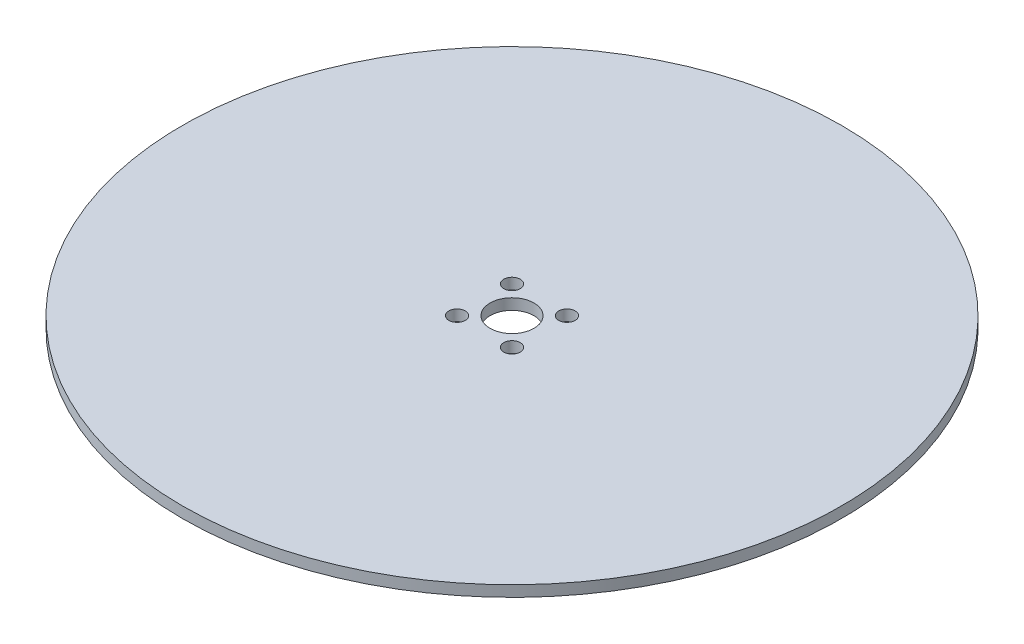
SolidWorks part; units mm, degrees
ref_plane "前视基准面" through (0, 0, 0) normal (0, 0, 1) x (1, 0, 0)
ref_plane "上视基准面" through (0, 0, 0) normal (0, 1, 0) x (1, 0, 0)
ref_plane "右视基准面" through (0, 0, 0) normal (1, 0, 0) x (0, 0, -1)
other "Configuration Table"
sketch "草图1" plane through (0, 0, 0) normal (0, 1, 0) x (1, 0, 0)
  circle A0 centre (0, 0) radius 60
  dimension "D1" = 120
extrude "凸台-拉伸1" add sketch "草图1" along normal blind 2
sketch "草图2" plane through (0, 2, 0) normal (0, 1, 0) x (1, 0, 0)
  line L1 (5, -5) -> (-5, -5)
  line L2 (5, -5) -> (5, 5)
  line L3 (5, 5) -> (-5, 5)
  line L4 (-5, -5) -> (-5, 5)
  line L5 (5, -5) -> (-5, 5) construction
  line L6 (5, 5) -> (-5, -5) construction
  circle A0 centre (-5, 5) radius 1.5
  circle A1 centre (5, 5) radius 1.5
  circle A2 centre (5, -5) radius 1.5
  circle A3 centre (-5, -5) radius 1.5
  circle A4 centre (0, 0) radius 4
  point P0 (0, 0)
  dimension "D3" = 3
  dimension "D4" = 3
  dimension "D5" = 3
  dimension "D6" = 3
  dimension "D7" = 8
  dimension "D1" = 10
  dimension "D2" = 10
extrude "切除-拉伸1" cut sketch "草图2" against normal blind 2 contours L3 A0 L4 | L4 A0 L3 | L2 A1 L3 | L3 A1 L2 | A4 | L2 A2 L1 | L1 A2 L2 | L4 A3 L1 | L1 A3 L4
